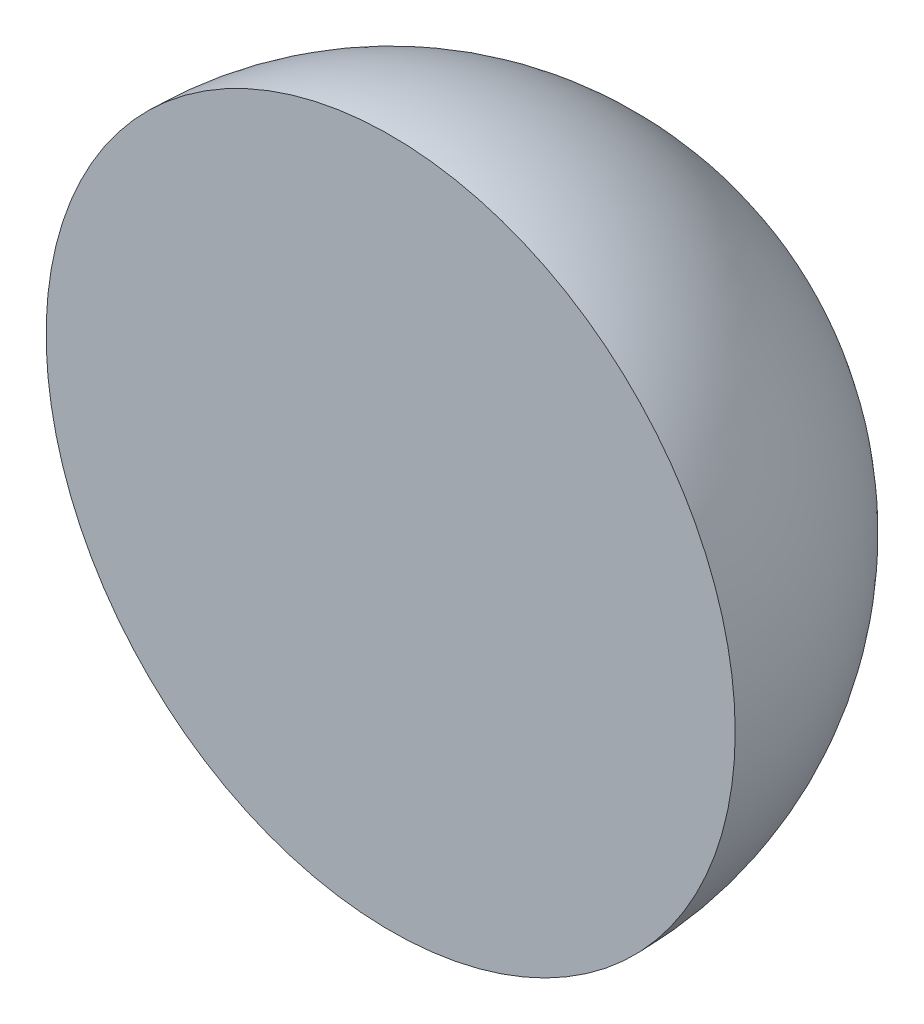
SolidWorks part; units mm, degrees
ref_plane "Front Plane" through (0, 0, 0) normal (0, 0, 1) x (1, 0, 0)
ref_plane "Top Plane" through (0, 0, 0) normal (0, 1, 0) x (1, 0, 0)
ref_plane "Right Plane" through (0, 0, 0) normal (1, 0, 0) x (0, 0, -1)
sketch "Sketch1" plane through (0, 0, 0) normal (0, 0, 1) x (1, 0, 0)
  line L0 (0, -5) -> (0, 5)
  arc A0 (0, 5) -> (0, -5) centre (0, 0) cw
  point P4 (0, 0)
revolve "Revolve1" add sketch "Sketch1" angle 180 about L0
